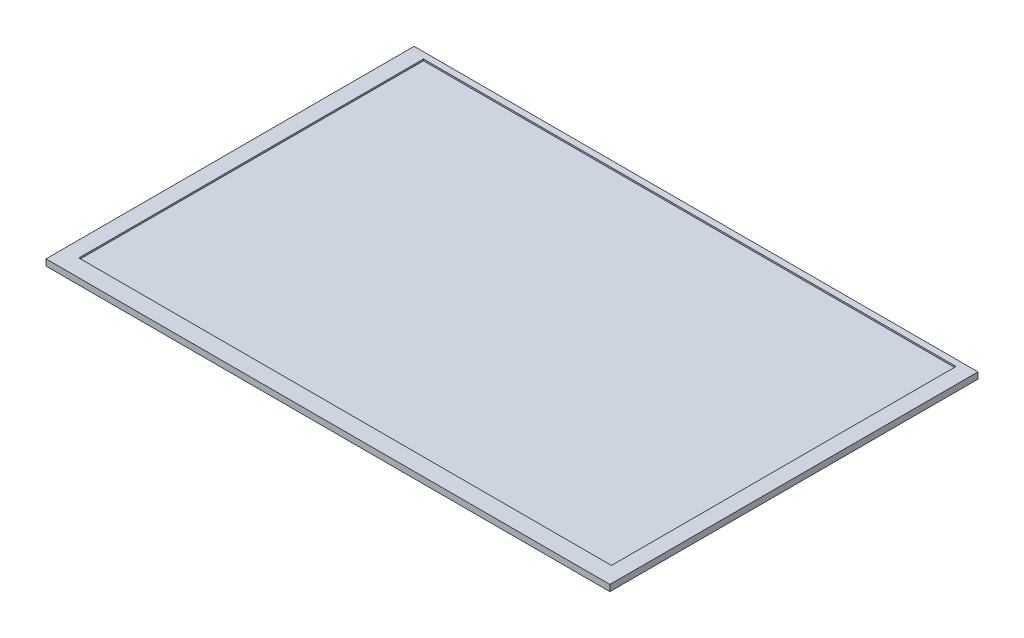
SolidWorks part; units mm, degrees
ref_plane "Front Plane" through (0, 0, 0) normal (0, 0, 1) x (1, 0, 0)
ref_plane "Top Plane" through (0, 0, 0) normal (0, 1, 0) x (1, 0, 0)
ref_plane "Right Plane" through (0, 0, 0) normal (1, 0, 0) x (0, 0, -1)
sketch "Sketch1" plane through (0, 0, 0) normal (0, 1, 0) x (1, 0, 0)
  line L1 (-114.3, -74.6125) -> (114.3, -74.6125)
  line L2 (-114.3, -74.6125) -> (-114.3, 74.6125)
  line L3 (-114.3, 74.6125) -> (114.3, 74.6125)
  line L4 (114.3, -74.6125) -> (114.3, 74.6125)
  line L5 (-114.3, -74.6125) -> (114.3, 74.6125) construction
  line L6 (-114.3, 74.6125) -> (114.3, -74.6125) construction
  point P0 (0, 0)
  dimension "D1" = 149.225
  dimension "D2" = 228.6
extrude "Boss-Extrude1" add sketch "Sketch1" along normal blind 2.54 contours L2 L3 L4 L1
sketch "Sketch2" plane through (0, 2.54, 0) normal (0, 1, 0) x (1, 0, 0)
  line L0 (114.3, -74.6125) -> (114.3, 74.6125) construction
  line L1 (107.95, -67.6275) -> (-107.95, -67.6275)
  line L2 (107.95, -67.6275) -> (107.95, 72.0725)
  line L3 (107.95, 72.0725) -> (-107.95, 72.0725)
  line L4 (-107.95, -67.6275) -> (-107.95, 72.0725)
  line L5 (-114.3, -74.6125) -> (-114.3, 74.6125) construction
  line L6 (-114.3, 74.6125) -> (114.3, 74.6125) construction
  line L7 (-114.3, -74.6125) -> (114.3, -74.6125) construction
  point P0 (0, 0)
  dimension "D1" = 6.35
  dimension "D2" = 6.985
  dimension "D3" = 6.35
  dimension "D4" = 2.54
extrude "Cut-Extrude1" cut sketch "Sketch2" against normal blind 0.635
